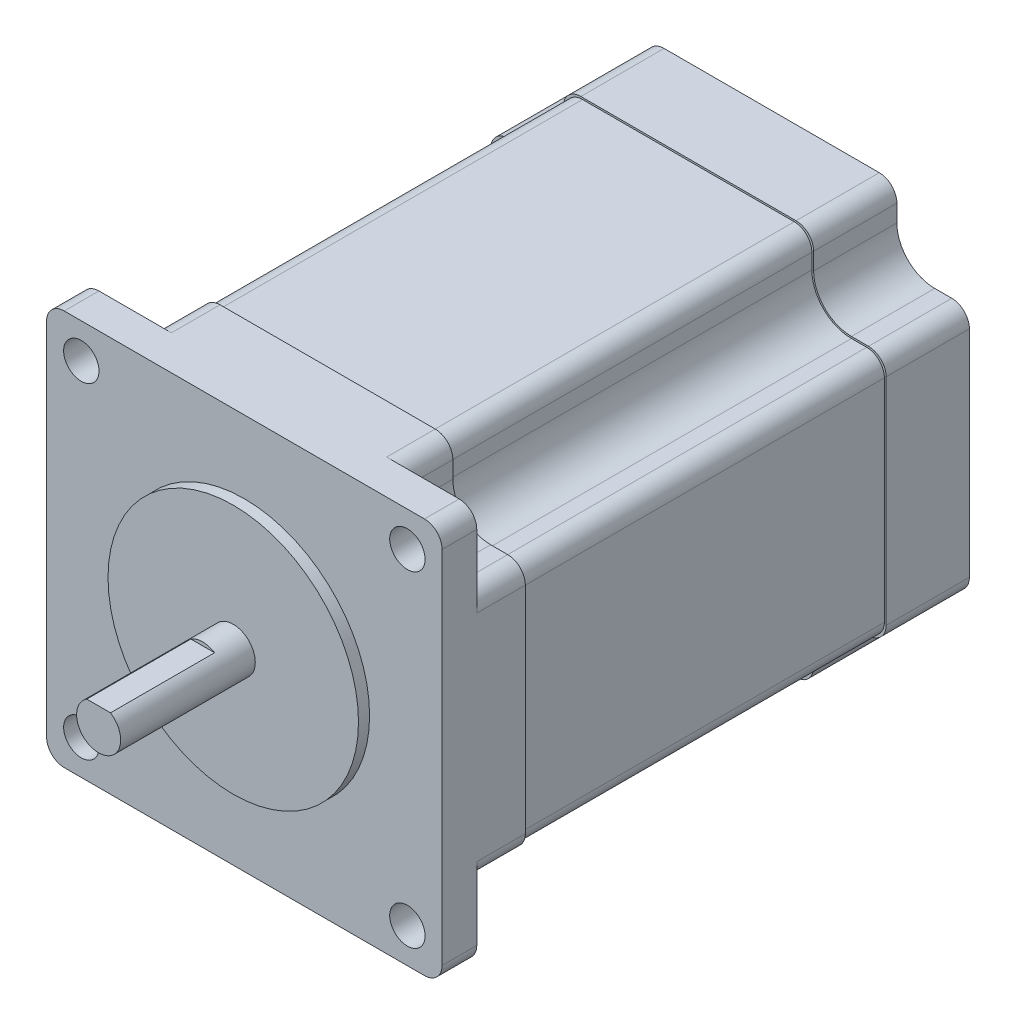
SolidWorks part; units mm, degrees
ref_plane "Front Plane" through (0, 0, 0) normal (0, 0, 1) x (1, 0, 0)
ref_plane "Top Plane" through (0, 0, 0) normal (0, 1, 0) x (1, 0, 0)
ref_plane "Right Plane" through (0, 0, 0) normal (1, 0, 0) x (0, 0, -1)
sketch "Sketch1" plane through (0, 0, 0) normal (0, 0, 1) x (1, 0, 0)
  line L1 (-28.5, -28.5) -> (28.5, -28.5)
  line L2 (-28.5, -28.5) -> (-28.5, 28.5)
  line L3 (-28.5, 28.5) -> (28.5, 28.5)
  line L4 (28.5, -28.5) -> (28.5, 28.5)
  line L5 (-28.5, -28.5) -> (28.5, 28.5) construction
  line L6 (-28.5, 28.5) -> (28.5, -28.5) construction
  line L7 (-23.5, -23.5) -> (23.5, -23.5) construction
  line L8 (-23.5, -23.5) -> (-23.5, 23.5) construction
  line L9 (-23.5, 23.5) -> (23.5, 23.5) construction
  line L10 (23.5, -23.5) -> (23.5, 23.5) construction
  line L11 (-23.5, -23.5) -> (23.5, 23.5) construction
  line L12 (-23.5, 23.5) -> (23.5, -23.5) construction
  circle A0 centre (-23.5, 23.5) radius 2.55
  circle A1 centre (23.5, 23.5) radius 2.55
  circle A2 centre (23.5, -23.5) radius 2.55
  circle A3 centre (-23.5, -23.5) radius 2.55
  point P0 (0, 0)
  point P6 (0, 0)
  dimension "D2" = 47
  dimension "D3" = 5.1
  dimension "D1" = 57
extrude "Boss-Extrude1" add sketch "Sketch1" against normal blind 5
sketch "Sketch2" plane through (0, 0, -5) normal (0, 0, -1) x (-1, 0, 0)
  line L0 (-18.05, 23.5) -> (-18.05, 28.5)
  line L1 (-28.5, 28.5) -> (28.5, 28.5) construction
  line L2 (-23.5, 18.05) -> (-28.5, 18.05)
  line L3 (-28.5, -28.5) -> (-28.5, 28.5) construction
  line L4 (38.7489, 0) -> (-45.3139, 0) construction
  line L5 (0, 37.0673) -> (0, -47.8439) construction
  line L6 (-23.5, -18.05) -> (-28.5, -18.05)
  line L7 (-18.05, -23.5) -> (-18.05, -28.5)
  line L8 (18.05, -23.5) -> (18.05, -28.5)
  line L9 (23.5, -18.05) -> (28.5, -18.05)
  line L10 (23.5, 18.05) -> (28.5, 18.05)
  line L11 (18.05, 23.5) -> (18.05, 28.5)
  line L12 (18.05, 28.5) -> (-18.05, 28.5)
  line L13 (-28.5, 18.05) -> (-28.5, -18.05)
  line L14 (-18.05, -28.5) -> (18.05, -28.5)
  line L15 (28.5, -18.05) -> (28.5, 18.05)
  arc A0 (-18.05, 23.5) -> (-23.5, 18.05) centre (-23.5, 23.5) cw
  arc A1 (-18.05, -23.5) -> (-23.5, -18.05) centre (-23.5, -23.5) ccw
  arc A2 (18.05, -23.5) -> (23.5, -18.05) centre (23.5, -23.5) cw
  arc A3 (18.05, 23.5) -> (23.5, 18.05) centre (23.5, 23.5) ccw
  dimension "D1" = 18.05
extrude "Boss-Extrude2" add sketch "Sketch2" along normal blind 7
sketch "Sketch5" plane through (0, 0, -12) normal (0, 0, -1) x (-1, 0, 0)
  line L24 (-23.5, 17.796) -> (-28.246, 17.796)
  line L25 (-28.246, 17.796) -> (-28.246, -17.796)
  line L26 (-28.246, -17.796) -> (-23.5, -17.796)
  line L27 (-17.796, -23.5) -> (-17.796, -28.246)
  line L28 (-17.796, -28.246) -> (17.796, -28.246)
  line L29 (17.796, -28.246) -> (17.796, -23.5)
  line L30 (23.5, -17.796) -> (28.246, -17.796)
  line L31 (28.246, -17.796) -> (28.246, 17.796)
  line L32 (28.246, 17.796) -> (23.5, 17.796)
  line L33 (17.796, 23.5) -> (17.796, 28.246)
  line L34 (17.796, 28.246) -> (-17.796, 28.246)
  line L35 (-17.796, 28.246) -> (-17.796, 23.5)
  line L36 (-23.5, 17.796) -> (-28.246, 17.796)
  line L37 (-28.246, 17.796) -> (-28.246, -17.796)
  line L38 (-28.246, -17.796) -> (-23.5, -17.796)
  line L39 (-17.796, -23.5) -> (-17.796, -28.246)
  line L40 (-17.796, -28.246) -> (17.796, -28.246)
  line L41 (17.796, -28.246) -> (17.796, -23.5)
  line L42 (23.5, -17.796) -> (28.246, -17.796)
  line L43 (28.246, -17.796) -> (28.246, 17.796)
  line L44 (28.246, 17.796) -> (23.5, 17.796)
  line L45 (17.796, 23.5) -> (17.796, 28.246)
  line L46 (17.796, 28.246) -> (-17.796, 28.246)
  line L47 (-17.796, 28.246) -> (-17.796, 23.5)
  arc A8 (-23.5, 17.796) -> (-17.796, 23.5) centre (-23.5, 23.5) ccw
  arc A9 (-17.796, -23.5) -> (-23.5, -17.796) centre (-23.5, -23.5) ccw
  arc A10 (23.5, -17.796) -> (17.796, -23.5) centre (23.5, -23.5) ccw
  arc A11 (17.796, 23.5) -> (23.5, 17.796) centre (23.5, 23.5) ccw
  arc A12 (-23.5, 17.796) -> (-17.796, 23.5) centre (-23.5, 23.5) ccw
  arc A13 (-17.796, -23.5) -> (-23.5, -17.796) centre (-23.5, -23.5) ccw
  arc A14 (23.5, -17.796) -> (17.796, -23.5) centre (23.5, -23.5) ccw
  arc A15 (17.796, 23.5) -> (23.5, 17.796) centre (23.5, 23.5) ccw
  dimension "D1" = 0.254
extrude "Boss-Extrude5" add sketch "Sketch5" along normal blind 52
sketch "Sketch6" plane through (0, 0, -64) normal (0, 0, -1) x (-1, 0, 0)
  line L24 (-23.5, 18.05) -> (-28.5, 18.05)
  line L25 (-28.5, 18.05) -> (-28.5, -18.05)
  line L26 (-28.5, -18.05) -> (-23.5, -18.05)
  line L27 (-18.05, -23.5) -> (-18.05, -28.5)
  line L28 (-18.05, -28.5) -> (18.05, -28.5)
  line L29 (18.05, -28.5) -> (18.05, -23.5)
  line L30 (23.5, -18.05) -> (28.5, -18.05)
  line L31 (28.5, -18.05) -> (28.5, 18.05)
  line L32 (28.5, 18.05) -> (23.5, 18.05)
  line L33 (18.05, 23.5) -> (18.05, 28.5)
  line L34 (18.05, 28.5) -> (-18.05, 28.5)
  line L35 (-18.05, 28.5) -> (-18.05, 23.5)
  line L36 (-23.5, 18.05) -> (-28.5, 18.05)
  line L37 (-28.5, 18.05) -> (-28.5, -18.05)
  line L38 (-28.5, -18.05) -> (-23.5, -18.05)
  line L39 (-18.05, -23.5) -> (-18.05, -28.5)
  line L40 (-18.05, -28.5) -> (18.05, -28.5)
  line L41 (18.05, -28.5) -> (18.05, -23.5)
  line L42 (23.5, -18.05) -> (28.5, -18.05)
  line L43 (28.5, -18.05) -> (28.5, 18.05)
  line L44 (28.5, 18.05) -> (23.5, 18.05)
  line L45 (18.05, 23.5) -> (18.05, 28.5)
  line L46 (18.05, 28.5) -> (-18.05, 28.5)
  line L47 (-18.05, 28.5) -> (-18.05, 23.5)
  arc A8 (-23.5, 18.05) -> (-18.05, 23.5) centre (-23.5, 23.5) ccw
  arc A9 (-18.05, -23.5) -> (-23.5, -18.05) centre (-23.5, -23.5) ccw
  arc A10 (23.5, -18.05) -> (18.05, -23.5) centre (23.5, -23.5) ccw
  arc A11 (18.05, 23.5) -> (23.5, 18.05) centre (23.5, 23.5) ccw
  arc A12 (-23.5, 18.05) -> (-18.05, 23.5) centre (-23.5, 23.5) ccw
  arc A13 (-18.05, -23.5) -> (-23.5, -18.05) centre (-23.5, -23.5) ccw
  arc A14 (23.5, -18.05) -> (18.05, -23.5) centre (23.5, -23.5) ccw
  arc A15 (18.05, 23.5) -> (23.5, 18.05) centre (23.5, 23.5) ccw
  dimension "D1" = 0.254
extrude "Boss-Extrude6" add sketch "Sketch6" along normal blind 12
sketch "Sketch7" plane through (0, 0, 0) normal (0, 0, 1) x (1, 0, 0)
  circle A0 centre (0, 0) radius 18.05
  dimension "D1" = 36.1
extrude "Boss-Extrude7" add sketch "Sketch7" along normal blind 1.6
sketch "Sketch8" plane through (0, 0, 0) normal (0, 0, 1) x (1, 0, 0)
  circle A0 centre (0, 0) radius 3.175
  dimension "D1" = 6.35
extrude "Boss-Extrude8" add sketch "Sketch8" along normal blind 21
sketch "Sketch9" plane through (0, 0, 0) normal (1, 0, 0) x (0, 0, -1)
  line L0 (-21, 3.175) -> (-21, -3.175) construction
  line L1 (-21, 3.175) -> (-6, 3.175)
  line L2 (-21, 3.175) -> (-21, 2.675)
  line L3 (-21, 2.675) -> (-6, 2.675)
  line L4 (-6, 3.175) -> (-6, 2.675)
  line L5 (-21, 3.175) -> (-6, 2.675) construction
  line L6 (-21, 2.675) -> (-6, 3.175) construction
  line L7 (-1.6, 3.175) -> (-21, 3.175) construction
  line L8 (-21, -3.175) -> (-1.6, -3.175) construction
  point P4 (-13.5, 2.925)
  dimension "D1" = 15
  dimension "D2" = 5.85
extrude "Cut-Extrude1" cut sketch "Sketch9" against normal mid plane 7
fillet "Fillet1" radius 2.54 28 edges at (-18.05, -28.5, -8.5) (-28.5, -18.05, -8.5) (-28.5, -18.05, -70) (-18.05, -28.5, -70) (-28.246, -17.796, -38) (-17.796, -28.246, -38) (18.05, -28.5, -70) (28.5, -18.05, -70) (28.246, -17.796, -38) (17.796, -28.246, -38) (18.05, -28.5, -8.5) (28.5, -18.05, -8.5) (28.5, 18.05, -70) (18.05, 28.5, -70) (18.05, 28.5, -8.5) (28.5, 18.05, -8.5) (28.246, 17.796, -38) (17.796, 28.246, -38) (-28.5, 18.05, -8.5) (-28.246, 17.796, -38) (-28.5, 18.05, -70) (-18.05, 28.5, -70) (-17.796, 28.246, -38) (-18.05, 28.5, -8.5) (-28.5, 28.5, -2.5) (-28.5, -28.5, -2.5) (28.5, -28.5, -2.5) (28.5, 28.5, -2.5)
